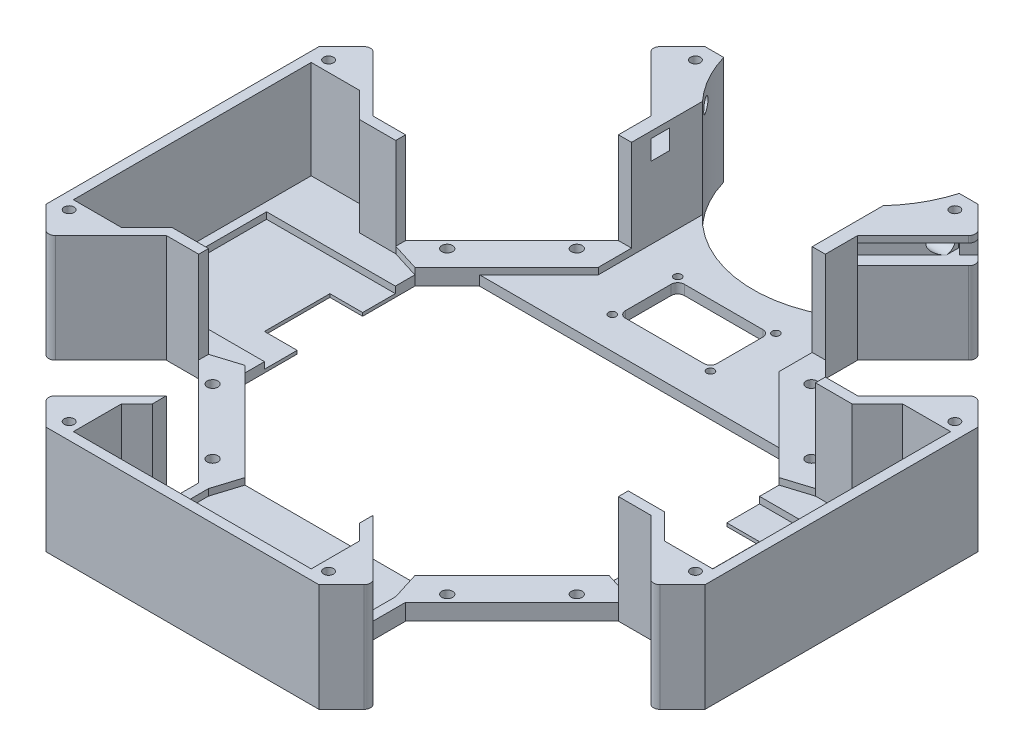
SolidWorks part; units mm, degrees
ref_plane "Front Plane" through (0, 0, 0) normal (0, 0, 1) x (1, 0, 0)
ref_plane "Top Plane" through (0, 0, 0) normal (0, 1, 0) x (1, 0, 0)
ref_plane "Right Plane" through (0, 0, 0) normal (1, 0, 0) x (0, 0, -1)
sketch "Sketch1" plane through (0, 0, 0) normal (0, 1, 0) x (1, 0, 0)
  line L1 (-41.7125, 100.7029) -> (-100.7029, 41.7125)
  line L2 (-100.7029, 41.7125) -> (-100.7029, -41.7125)
  line L3 (-100.7029, -41.7125) -> (-41.7125, -100.7029)
  line L4 (-41.7125, -100.7029) -> (41.7125, -100.7029)
  line L5 (41.7125, -100.7029) -> (100.7029, -41.7125)
  line L6 (100.7029, -41.7125) -> (100.7029, 41.7125)
  line L7 (100.7029, 41.7125) -> (41.7125, 100.7029)
  line L8 (41.7125, 100.7029) -> (-41.7125, 100.7029)
  circle A0 centre (0, 0) radius 100.7029 construction
  circle A1 centre (0, 0) radius 109 construction
  dimension "D1" = 218
extrude "Boss-Extrude1" add sketch "Sketch1" along normal blind 3
sketch "Sketch2" plane through (0, 3, 0) normal (0, 1, 0) x (1, 0, 0)
  line L5 (-92.4209, 49.9945) -> (-49.9945, 92.4209)
  line L6 (-92.4209, 49.9945) -> (-69.0864, 26.66)
  line L7 (-49.9945, 92.4209) -> (-26.66, 69.0864)
  line L8 (-69.0864, 26.66) -> (-26.66, 69.0864)
  line L9 (-41.7125, 100.7029) -> (-100.7029, 41.7125) construction
  line L10 (0, 0) -> (-71.2077, 71.2077) construction
  line L11 (100.7029, 41.7125) -> (41.7125, 100.7029) construction
  line L12 (49.9945, 92.4209) -> (92.4209, 49.9945)
  line L13 (49.9945, 92.4209) -> (26.66, 69.0864)
  line L14 (26.66, 69.0864) -> (69.0864, 26.66)
  line L15 (92.4209, 49.9945) -> (69.0864, 26.66)
  line L16 (92.4209, -49.9945) -> (49.9945, -92.4209)
  line L17 (92.4209, -49.9945) -> (69.0864, -26.66)
  line L18 (69.0864, -26.66) -> (26.66, -69.0864)
  line L19 (49.9945, -92.4209) -> (26.66, -69.0864)
  line L20 (-49.9945, -92.4209) -> (-92.4209, -49.9945)
  line L21 (-49.9945, -92.4209) -> (-26.66, -69.0864)
  line L22 (-26.66, -69.0864) -> (-69.0864, -26.66)
  line L23 (-92.4209, -49.9945) -> (-69.0864, -26.66)
  circle A0 centre (-55.6513, 35.8523) radius 1.65
  circle A1 centre (-35.8523, 55.6513) radius 1.65
  circle A2 centre (55.6513, 35.8523) radius 1.65
  circle A3 centre (35.8523, 55.6513) radius 1.65
  circle A4 centre (35.8523, -55.6513) radius 1.65
  circle A5 centre (55.6513, -35.8523) radius 1.65
  circle A6 centre (-55.6513, -35.8523) radius 1.65
  circle A7 centre (-35.8523, -55.6513) radius 1.65
  point P42 (0, 0)
  dimension "D7" = 3.3
  dimension "D8" = 3.3
  dimension "D1" = 60
  dimension "D2" = 33
  dimension "D3" = 3
  dimension "D4" = 3
  dimension "D5" = 28
  dimension "D6" = 14
  dimension "D10" = 71.7047
  dimension "D11" = 67.7029
  dimension "D9" = 4
extrude "Cut-Extrude1" cut sketch "Sketch2" against normal up to next
sketch "Sketch3" plane through (0, 3, 0) normal (0, 1, 0) x (1, 0, 0)
  line L0 (0, 0) -> (0, 50000) construction
  line L1 (-1015.9137, 73.7029) -> (48984.0863, 73.7029) construction
  line L2 (41.7125, 100.7029) -> (-41.7125, 100.7029) construction
  circle A0 centre (0, 111.2029) radius 37.5
  dimension "D1" = 75
  dimension "D2" = 27
extrude "Cut-Extrude2" cut sketch "Sketch3" against normal up to next
chamfer "Chamfer1" distance 8 angle 45 8 edges at (92.4209, 1.5, 49.9945) (49.9945, 1.5, 92.4209) (-49.9945, 1.5, 92.4209) (-92.4209, 1.5, 49.9945) (-92.4209, 1.5, -49.9945) (92.4209, 1.5, -49.9945) (-49.9945, 1.5, -92.4209) (49.9945, 1.5, -92.4209)
chamfer "Chamfer2" distance 7 angle 45 8 edges at (-69.0864, 1.5, 26.66) (-26.66, 1.5, 69.0864) (26.66, 1.5, 69.0864) (69.0864, 1.5, 26.66) (69.0864, 1.5, -26.66) (26.66, 1.5, -69.0864) (-69.0864, 1.5, -26.66) (-26.66, 1.5, -69.0864)
sketch "Sketch4" plane through (0, 3, 0) normal (0, 1, 0) x (1, 0, 0)
  line L0 (-36, 100.7029) -> (-41.7125, 100.7029) construction
  line L1 (-41.7125, 100.7029) -> (-44.3376, 98.0777) construction
  line L2 (41.7125, 100.7029) -> (36, 100.7029) construction
  line L3 (44.3376, 98.0777) -> (41.7125, 100.7029) construction
  circle A0 centre (-39.6414, 95.7029) radius 1.5
  circle A1 centre (39.6414, 95.7029) radius 1.5
  circle A2 centre (95.7029, 39.6414) radius 1.5
  circle A3 centre (95.7029, -39.6414) radius 1.5
  circle A4 centre (39.6414, -95.7029) radius 1.5
  circle A5 centre (-39.6414, -95.7029) radius 1.5
  circle A6 centre (-95.7029, -39.6414) radius 1.5
  circle A7 centre (-95.7029, 39.6414) radius 1.5
  point P22 (0, 0)
  dimension "D3" = 3
  dimension "D1" = 5
  dimension "D2" = 5
  dimension "D5" = 5
  dimension "D6" = 5
  dimension "D4" = 8
extrude "Cut-Extrude3" cut sketch "Sketch4" against normal up to next
sketch "Sketch5" plane through (0, 3, 0) normal (0, 1, 0) x (1, 0, 0)
  line L0 (-45.7518, 35.8523) -> (-55.6513, 25.9528)
  line L1 (-55.6513, 25.9528) -> (-55.6513, -25.9528)
  line L2 (-55.6513, -25.9528) -> (-25.9528, -55.6513)
  line L3 (-25.9528, -55.6513) -> (25.9528, -55.6513)
  line L4 (25.9528, -55.6513) -> (55.6513, -25.9528)
  line L5 (55.6513, -25.9528) -> (55.6513, 25.9528)
  line L6 (55.6513, 25.9528) -> (45.7518, 35.8523)
  line L7 (45.7518, 35.8523) -> (-45.7518, 35.8523)
  line L8 (-55.6513, 35.8523) -> (55.6513, 35.8523) construction
  line L9 (55.6513, 35.8523) -> (55.6513, -35.8523) construction
  line L10 (55.6513, -35.8523) -> (35.8523, -55.6513) construction
  line L11 (35.8523, -55.6513) -> (-35.8523, -55.6513) construction
  line L12 (-35.8523, -55.6513) -> (-55.6513, -35.8523) construction
  line L13 (-55.6513, -35.8523) -> (-55.6513, 35.8523) construction
  line L14 (-64.1366, 31.6097) -> (-31.6097, 64.1366) construction
  line L15 (31.6097, 64.1366) -> (64.1366, 31.6097) construction
  line L16 (-31.6097, -64.1366) -> (-64.1366, -31.6097) construction
  line L17 (64.1366, -31.6097) -> (31.6097, -64.1366) construction
  dimension "D1" = 10
  dimension "D2" = 10
  dimension "D3" = 10
  dimension "D4" = 10
extrude "Cut-Extrude4" cut sketch "Sketch5" against normal up to next
sketch "Sketch7" plane through (0, 3, 0) normal (0, 1, 0) x (1, 0, 0)
  line L0 (-64.1366, 31.6097) -> (-74.0361, 31.6097)
  line L1 (-74.0361, 31.6097) -> (-86.764, 44.3376)
  line L2 (-86.764, 44.3376) -> (-98.0777, 44.3376)
  line L3 (-98.0777, 44.3376) -> (-100.7029, 41.7125)
  line L4 (-100.7029, 41.7125) -> (-100.7029, -41.7125)
  line L5 (-100.7029, -41.7125) -> (-98.0777, -44.3376)
  line L6 (-98.0777, -44.3376) -> (-86.764, -44.3376)
  line L7 (-86.764, -44.3376) -> (-74.0361, -31.6097)
  line L8 (-74.0361, -31.6097) -> (-64.1366, -31.6097)
  line L9 (-64.1366, -31.6097) -> (-64.1366, -28.6097)
  line L10 (-64.1366, -28.6097) -> (-75.2787, -28.6097)
  line L11 (-75.2787, -28.6097) -> (-83.0067, -36.3376)
  line L12 (-83.0067, -36.3376) -> (-97.7029, -36.3376)
  line L13 (-97.7029, -36.3376) -> (-97.7029, 36.3376)
  line L14 (-97.7029, 36.3376) -> (-83.0067, 36.3376)
  line L15 (-83.0067, 36.3376) -> (-75.2787, 28.6097)
  line L16 (-75.2787, 28.6097) -> (-64.1366, 28.6097)
  line L17 (-64.1366, 28.6097) -> (-64.1366, 31.6097)
  line L18 (-31.6097, -64.1366) -> (-31.6097, -74.0361)
  line L19 (-31.6097, -74.0361) -> (-44.3376, -86.764)
  line L20 (-44.3376, -86.764) -> (-44.3376, -98.0777)
  line L21 (-44.3376, -98.0777) -> (-41.7125, -100.7029)
  line L22 (-41.7125, -100.7029) -> (41.7125, -100.7029)
  line L23 (41.7125, -100.7029) -> (44.3376, -98.0777)
  line L24 (44.3376, -98.0777) -> (44.3376, -86.764)
  line L25 (44.3376, -86.764) -> (31.6097, -74.0361)
  line L26 (31.6097, -74.0361) -> (31.6097, -64.1366)
  line L27 (31.6097, -64.1366) -> (28.6097, -64.1366)
  line L28 (28.6097, -64.1366) -> (28.6097, -75.2787)
  line L29 (28.6097, -75.2787) -> (36.3376, -83.0067)
  line L30 (36.3376, -83.0067) -> (36.3376, -97.7029)
  line L31 (36.3376, -97.7029) -> (-36.3376, -97.7029)
  line L32 (-36.3376, -97.7029) -> (-36.3376, -83.0067)
  line L33 (-36.3376, -83.0067) -> (-28.6097, -75.2787)
  line L34 (-28.6097, -75.2787) -> (-28.6097, -64.1366)
  line L35 (-28.6097, -64.1366) -> (-31.6097, -64.1366)
  line L36 (64.1366, -31.6097) -> (74.0361, -31.6097)
  line L37 (74.0361, -31.6097) -> (86.764, -44.3376)
  line L38 (86.764, -44.3376) -> (98.0777, -44.3376)
  line L39 (98.0777, -44.3376) -> (100.7029, -41.7125)
  line L40 (100.7029, -41.7125) -> (100.7029, 41.7125)
  line L41 (100.7029, 41.7125) -> (98.0777, 44.3376)
  line L42 (98.0777, 44.3376) -> (86.764, 44.3376)
  line L43 (86.764, 44.3376) -> (74.0361, 31.6097)
  line L44 (74.0361, 31.6097) -> (64.1366, 31.6097)
  line L45 (64.1366, 31.6097) -> (64.1366, 28.6097)
  line L46 (64.1366, 28.6097) -> (75.2787, 28.6097)
  line L47 (75.2787, 28.6097) -> (83.0067, 36.3376)
  line L48 (83.0067, 36.3376) -> (97.7029, 36.3376)
  line L49 (97.7029, 36.3376) -> (97.7029, -36.3376)
  line L50 (97.7029, -36.3376) -> (83.0067, -36.3376)
  line L51 (83.0067, -36.3376) -> (75.2787, -28.6097)
  line L52 (75.2787, -28.6097) -> (64.1366, -28.6097)
  line L53 (64.1366, -28.6097) -> (64.1366, -31.6097)
  line L54 (0, 0) -> (-64.1366, 28.6097) construction
  line L55 (0, 0) -> (-28.6097, -64.1366) construction
  line L57 (-36, 100.7029) -> (-41.7125, 100.7029)
  line L58 (-41.7125, 100.7029) -> (-44.3376, 98.0777)
  line L59 (-44.3376, 98.0777) -> (-44.3376, 86.764)
  line L60 (-44.3376, 86.764) -> (-31.6097, 74.0361)
  line L61 (-31.6097, 74.0361) -> (-31.6097, 64.1366)
  line L62 (-31.6097, 64.1366) -> (-27.6097, 64.1366)
  line L63 (-27.6097, 64.1366) -> (-27.6097, 85.8266)
  line L64 (0, -888.7971) -> (0, 49111.2029) construction
  line L65 (27.6097, 64.1366) -> (27.6097, 85.8266)
  line L66 (31.6097, 64.1366) -> (27.6097, 64.1366)
  line L67 (31.6097, 74.0361) -> (31.6097, 64.1366)
  line L68 (44.3376, 86.764) -> (31.6097, 74.0361)
  line L69 (44.3376, 98.0777) -> (44.3376, 86.764)
  line L70 (41.7125, 100.7029) -> (44.3376, 98.0777)
  line L71 (36, 100.7029) -> (41.7125, 100.7029)
  arc A0 (-36, 100.7029) -> (-27.6097, 85.8266) centre (0, 111.2029) ccw
  arc A1 (36, 100.7029) -> (27.6097, 85.8266) centre (0, 111.2029) cw
  circle A10 centre (-39.6414, 95.7029) radius 1.5
  circle A11 centre (39.6414, 95.7029) radius 1.5
  circle A12 centre (95.7029, 39.6414) radius 1.5
  circle A13 centre (95.7029, -39.6414) radius 1.5
  circle A14 centre (39.6414, -95.7029) radius 1.5
  circle A15 centre (-39.6414, -95.7029) radius 1.5
  circle A16 centre (-95.7029, -39.6414) radius 1.5
  circle A17 centre (-95.7029, 39.6414) radius 1.5
  point P4 (-92.4209, 44.3376)
  point P29 (-92.4209, -44.3376)
  dimension "D14" = 3
  dimension "D15" = 3
  dimension "D16" = 3
  dimension "D17" = 3
  dimension "D18" = 3
  dimension "D19" = 3
  dimension "D20" = 3
  dimension "D21" = 3
  dimension "D1" = 3
  dimension "D2" = 8
  dimension "D3" = 8
  dimension "D4" = 3
  dimension "D5" = 3
  dimension "D6" = 3
  dimension "D7" = 3
  dimension "D9" = 90
  dimension "D10" = 90
  dimension "D11" = 28.6097
  dimension "D12" = 64.1366
  dimension "D13" = 4
  dimension "D8" = 3
extrude "Boss-Extrude2" add sketch "Sketch7" along normal blind 30
sketch "Sketch8" plane through (0, 0, 0) normal (0, -1, 0) x (1, 0, 0)
  line L0 (-41.7125, 100.7029) -> (41.7125, 100.7029) construction
  line L1 (-22, 83.7029) -> (-2, 83.7029)
  line L2 (-22, 83.7029) -> (-22, 95.7029)
  line L3 (-22, 95.7029) -> (-2, 95.7029)
  line L4 (-2, 83.7029) -> (-2, 95.7029)
  line L5 (-22, 83.7029) -> (-2, 95.7029) construction
  line L6 (-22, 95.7029) -> (-2, 83.7029) construction
  line L7 (0, -1000) -> (0, 49000) construction
  line L8 (22, 95.7029) -> (2, 83.7029) construction
  line L9 (22, 83.7029) -> (2, 95.7029) construction
  line L10 (2, 83.7029) -> (2, 95.7029)
  line L11 (22, 95.7029) -> (2, 95.7029)
  line L12 (22, 83.7029) -> (22, 95.7029)
  line L13 (22, 83.7029) -> (2, 83.7029)
  point P0 (-12, 89.7029)
  point P15 (12, 89.7029)
  dimension "D1" = 20
  dimension "D2" = 12
  dimension "D3" = 5
  dimension "D4" = 2
extrude "Cut-Extrude5" cut sketch "Sketch8" against normal up to next
sketch "Sketch10" plane through (0, 3, 0) normal (0, 1, 0) x (1, 0, 0)
  line L1 (-95, -20) -> (95, -20)
  line L2 (-95, -20) -> (-95, 20)
  line L3 (-95, 20) -> (95, 20)
  line L4 (95, -20) -> (95, 20)
  line L5 (-95, -20) -> (95, 20) construction
  line L6 (-95, 20) -> (95, -20) construction
  point P0 (0, 0)
  dimension "D1" = 190
  dimension "D2" = 40
extrude "Cut-Extrude6" cut sketch "Sketch10" against normal blind 2
sketch "Sketch11" plane through (0, 3, 0) normal (0, 1, 0) x (1, 0, 0)
  line L0 (-31.6097, 64.1366) -> (-64.1366, 31.6097)
  line L1 (-64.1366, 31.6097) -> (-64.1366, 28.6097)
  line L2 (-64.1366, 28.6097) -> (-55.6513, 25.9528)
  line L3 (-55.6513, 25.9528) -> (-27.6097, 53.9945)
  line L4 (-27.6097, 53.9945) -> (-27.6097, 64.1366)
  line L5 (-27.6097, 64.1366) -> (-31.6097, 64.1366)
  line L6 (-28.6097, -64.1366) -> (-25.9528, -55.6513)
  line L7 (-25.9528, -55.6513) -> (-55.6513, -25.9528)
  line L8 (-55.6513, -25.9528) -> (-64.1366, -28.6097)
  line L9 (-64.1366, -28.6097) -> (-64.1366, -31.6097)
  line L10 (-64.1366, -31.6097) -> (-31.6097, -64.1366)
  line L11 (-31.6097, -64.1366) -> (-28.6097, -64.1366)
  line L12 (0, -1000) -> (0, 49000) construction
  line L13 (31.6097, -64.1366) -> (28.6097, -64.1366)
  line L14 (64.1366, -31.6097) -> (31.6097, -64.1366)
  line L15 (64.1366, -28.6097) -> (64.1366, -31.6097)
  line L16 (55.6513, -25.9528) -> (64.1366, -28.6097)
  line L17 (25.9528, -55.6513) -> (55.6513, -25.9528)
  line L18 (28.6097, -64.1366) -> (25.9528, -55.6513)
  line L19 (27.6097, 64.1366) -> (31.6097, 64.1366)
  line L20 (27.6097, 53.9945) -> (27.6097, 64.1366)
  line L21 (55.6513, 25.9528) -> (27.6097, 53.9945)
  line L22 (64.1366, 28.6097) -> (55.6513, 25.9528)
  line L23 (64.1366, 31.6097) -> (64.1366, 28.6097)
  line L24 (31.6097, 64.1366) -> (64.1366, 31.6097)
  circle A0 centre (-35.8523, 55.6513) radius 1.65
  circle A1 centre (-55.6513, 35.8523) radius 1.65
  circle A2 centre (-55.6513, -35.8523) radius 1.65
  circle A3 centre (-35.8523, -55.6513) radius 1.65
  circle A4 centre (35.8523, -55.6513) radius 1.65
  circle A5 centre (55.6513, -35.8523) radius 1.65
  circle A6 centre (55.6513, 35.8523) radius 1.65
  circle A7 centre (35.8523, 55.6513) radius 1.65
  dimension "D1" = 3.3
  dimension "D2" = 3.3
  dimension "D3" = 3.3
  dimension "D4" = 3.3
  dimension "D5" = 3.3
  dimension "D6" = 3.3
  dimension "D7" = 3.3
  dimension "D8" = 3.3
extrude "Boss-Extrude4" add sketch "Sketch11" along normal blind 2
sketch "Sketch12" plane through (0, 33, 0) normal (0, 1, 0) x (1, 0, 0)
  line L0 (-36.3376, -83.0067) -> (-28.6097, -75.2787) construction
  line L1 (-28.6097, -64.1366) -> (-31.6097, -64.1366)
  line L2 (-28.6097, -64.1366) -> (-28.6097, -78.2787)
  line L3 (-28.6097, -78.2787) -> (-31.6097, -78.2787)
  line L4 (-31.6097, -64.1366) -> (-31.6097, -78.2787)
  line L5 (-31.6097, -64.1366) -> (-31.6097, -74.0361) construction
  line L6 (28.6097, -75.2787) -> (36.3376, -83.0067) construction
  line L7 (28.6097, -64.1366) -> (31.6097, -64.1366)
  line L8 (28.6097, -64.1366) -> (28.6097, -78.2787)
  line L9 (28.6097, -78.2787) -> (31.6097, -78.2787)
  line L10 (31.6097, -64.1366) -> (31.6097, -78.2787)
  line L11 (31.6097, -74.0361) -> (31.6097, -64.1366) construction
extrude "Cut-Extrude7" cut sketch "Sketch12" against normal up to surface (28 mm away) up to face at (-45.0161, 5, 45.0161)
sketch "Sketch13" plane through (0, 0, 0) normal (0, -1, 0) x (-1, 0, 0)
  line L0 (35.8523, 55.6513) -> (-35.8523, 55.6513) construction
  line L1 (15, 65.6513) -> (-15, 65.6513) construction
  line L2 (15, 65.6513) -> (15, 45.6513) construction
  line L3 (15, 45.6513) -> (-15, 45.6513) construction
  line L4 (-15, 65.6513) -> (-15, 45.6513) construction
  line L5 (15, 65.6513) -> (-15, 45.6513) construction
  line L6 (15, 45.6513) -> (-15, 65.6513) construction
  line L9 (12, 64.6513) -> (-12, 64.6513)
  line L10 (14, 62.6513) -> (14, 48.6513)
  line L11 (12, 46.6513) -> (-12, 46.6513)
  line L12 (-14, 62.6513) -> (-14, 48.6513)
  line L13 (14, 64.6513) -> (-14, 46.6513) construction
  line L14 (14, 46.6513) -> (-14, 64.6513) construction
  circle A1 centre (15, 45.6513) radius 1.15
  circle A2 centre (-15, 45.6513) radius 1.15
  circle A3 centre (15, 65.6513) radius 1.15
  circle A4 centre (-15, 65.6513) radius 1.15
  arc A5 (12, 64.6513) -> (14, 62.6513) centre (12, 62.6513) cw
  arc A6 (-12, 64.6513) -> (-14, 62.6513) centre (-12, 62.6513) ccw
  arc A7 (-12, 46.6513) -> (-14, 48.6513) centre (-12, 48.6513) cw
  arc A8 (14, 48.6513) -> (12, 46.6513) centre (12, 48.6513) cw
  point P0 (0, 55.6513)
  point P14 (0, 55.6513)
  dimension "D3" = 2.3
  dimension "D4" = 2.3
  dimension "D5" = 2.3
  dimension "D6" = 2.3
  dimension "D9" = 2
  dimension "D1" = 20
  dimension "D2" = 30
  dimension "D7" = 2
  dimension "D8" = 2
extrude "Cut-Extrude8" cut sketch "Sketch13" against normal up to next
sketch "Sketch14" plane through (-44.3376, 0, 0) normal (-1, 0, 0) x (0, 0, 1)
  line L1 (-86.764, 33) -> (-86.764, 0) construction
  line L2 (-98.0777, 33) -> (-86.764, 33) construction
  circle A0 centre (-90.264, 28) radius 2
  dimension "D3" = 4
  dimension "D1" = 5
  dimension "D2" = 3.5
extrude "Cut-Extrude9" cut sketch "Sketch14" against normal through all both and the other way through all
sketch "Sketch15" plane through (-44.3376, 0, 0) normal (-1, 0, 0) x (0, 0, 1)
  circle A0 centre (-90.264, 28) radius 3
  dimension "D1" = 6
extrude "Cut-Extrude10" cut sketch "Sketch15" against normal blind 10
sketch "Sketch16" plane through (0, 0, -64.1366) normal (0, 0, 1) x (1, 0, 0)
  line L0 (-44.3376, 33) -> (-44.3376, 0) construction
  line L1 (-44.3376, 31) -> (-42.3376, 31)
  line L2 (-44.3376, 31) -> (-44.3376, 25)
  line L3 (-44.3376, 25) -> (-42.3376, 25)
  line L4 (-42.3376, 31) -> (-42.3376, 25)
  line L5 (-44.3376, 33) -> (-31.6097, 33) construction
  dimension "D1" = 2
  dimension "D2" = 6
  dimension "D3" = 2
extrude "Cut-Extrude11" cut sketch "Sketch16" against normal blind 30
sketch "Sketch17" plane through (44.3376, 0, 0) normal (1, 0, 0) x (0, 0, -1)
  circle A0 centre (90.264, 28) radius 3
  dimension "D1" = 6
extrude "Cut-Extrude12" cut sketch "Sketch17" against normal blind 10
sketch "Sketch18" plane through (0, 0, -64.1366) normal (0, 0, 1) x (1, 0, 0)
  line L0 (44.3376, 0) -> (44.3376, 33) construction
  line L1 (44.3376, 31) -> (42.3376, 31)
  line L2 (44.3376, 31) -> (44.3376, 25)
  line L3 (44.3376, 25) -> (42.3376, 25)
  line L4 (42.3376, 31) -> (42.3376, 25)
  dimension "D1" = 2
  dimension "D2" = 6
  dimension "D3" = 2
extrude "Cut-Extrude13" cut sketch "Sketch18" against normal blind 30 contours L2 L3 L4 L1
sketch "Sketch21" plane through (0, 0, 0) normal (0, 1, 0) x (1, 0, 0)
  line L0 (-98.0777, 44.3376) -> (-93.8351, 48.5803)
  line L1 (-91.0067, 48.5803) -> (-86.764, 44.3376)
  line L2 (-86.764, 44.3376) -> (-98.0777, 44.3376)
  line L3 (-44.3376, 86.764) -> (-48.5803, 91.0067)
  line L4 (-48.5803, 93.8351) -> (-44.3376, 98.0777)
  line L5 (-44.3376, 98.0777) -> (-44.3376, 86.764)
  line L6 (44.3376, 86.764) -> (48.5803, 91.0067)
  line L7 (48.5803, 93.8351) -> (44.3376, 98.0777)
  line L8 (44.3376, 98.0777) -> (44.3376, 86.764)
  line L9 (86.764, 44.3376) -> (91.0067, 48.5803)
  line L10 (93.8351, 48.5803) -> (98.0777, 44.3376)
  line L11 (98.0777, 44.3376) -> (86.764, 44.3376)
  line L12 (86.764, -44.3376) -> (91.0067, -48.5803)
  line L13 (93.8351, -48.5803) -> (98.0777, -44.3376)
  line L14 (98.0777, -44.3376) -> (86.764, -44.3376)
  line L15 (44.3376, -86.764) -> (48.5803, -91.0067)
  line L16 (48.5803, -93.8351) -> (44.3376, -98.0777)
  line L17 (44.3376, -98.0777) -> (44.3376, -86.764)
  line L18 (44.3376, -86.764) -> (31.6097, -74.0361) construction
  line L19 (100.7029, 41.7125) -> (98.0777, 44.3376) construction
  line L20 (-74.0361, 31.6097) -> (-86.764, 44.3376) construction
  line L21 (-44.3376, -98.0777) -> (-48.5803, -93.8351)
  line L22 (-48.5803, -91.0067) -> (-44.3376, -86.764)
  line L23 (-44.3376, -86.764) -> (-44.3376, -98.0777)
  line L24 (-44.3376, -98.0777) -> (-41.7125, -100.7029) construction
  line L25 (-98.0777, -44.3376) -> (-93.8351, -48.5803)
  line L26 (-91.0067, -48.5803) -> (-86.764, -44.3376)
  line L27 (-86.764, -44.3376) -> (-98.0777, -44.3376)
  line L28 (-86.764, -44.3376) -> (-74.0361, -31.6097) construction
  line L29 (-100.7029, -41.7125) -> (-98.0777, -44.3376) construction
  arc A0 (-93.8351, -48.5803) -> (-91.0067, -48.5803) centre (-92.4209, -47.1661) ccw
  arc A1 (-48.5803, -93.8351) -> (-48.5803, -91.0067) centre (-47.1661, -92.4209) cw
  arc A2 (48.5803, -91.0067) -> (48.5803, -93.8351) centre (47.1661, -92.4209) cw
  arc A3 (91.0067, -48.5803) -> (93.8351, -48.5803) centre (92.4209, -47.1661) ccw
  arc A4 (91.0067, 48.5803) -> (93.8351, 48.5803) centre (92.4209, 47.1661) cw
  arc A5 (48.5803, 91.0067) -> (48.5803, 93.8351) centre (47.1661, 92.4209) ccw
  arc A6 (-93.8351, 48.5803) -> (-91.0067, 48.5803) centre (-92.4209, 47.1661) cw
  arc A7 (-48.5803, 91.0067) -> (-48.5803, 93.8351) centre (-47.1661, 92.4209) cw
  dimension "D1" = 2
extrude "Boss-Extrude5" add sketch "Sketch21" along normal up to surface (33 mm away) up to face at (-95.7029, 33, 41.1414)
sketch "Sketch22" plane through (71.2077, 0, -71.2077) normal (0.7071, 0, -0.7071) x (-0.7071, 0, -0.7071)
  line L0 (30, 33) -> (30, 0) construction
  line L1 (30, 31) -> (34, 31)
  line L2 (30, 31) -> (30, 25)
  line L3 (30, 25) -> (34, 25)
  line L4 (34, 31) -> (34, 25)
  line L5 (32, 33) -> (32, 0) construction
  point P8 (0, 0)
  point P15 (0, 0)
  dimension "D1" = 2
extrude "Cut-Extrude15" cut sketch "Sketch22" against normal up to surface (27.6569 mm away)
sketch "Sketch23" plane through (0, 0, -100.7029) normal (0, 0, -1) x (-1, 0, 0)
  line L0 (-41.7125, 33) -> (-41.7125, 0) construction
  line L1 (-41.7125, 31) -> (-49.1661, 31)
  line L2 (-41.7125, 31) -> (-41.7125, 25)
  line L3 (-41.7125, 25) -> (-49.1661, 25)
  line L4 (-49.1661, 31) -> (-49.1661, 25)
  line L5 (-47.1661, 31) -> (-48.5803, 31) construction
sketch "Sketch24" plane through (-71.2077, 0, -71.2077) normal (-0.7071, 0, -0.7071) x (-0.7071, 0, 0.7071)
  line L0 (-30, 0) -> (-30, 33) construction
  line L1 (-30, 31) -> (-34, 31)
  line L2 (-30, 31) -> (-30, 25)
  line L3 (-30, 25) -> (-34, 25)
  line L4 (-34, 31) -> (-34, 25)
  line L5 (-32, 33) -> (-32, 0) construction
  dimension "D1" = 2
extrude "Cut-Extrude17" cut sketch "Sketch24" against normal up to surface (31.6569 mm away)
sketch "Sketch25" plane through (0, 1, 0) normal (0, 1, 0) x (1, 0, 0)
  line L0 (-55.6513, 20) -> (-55.6513, -20) construction
  line L1 (-65.6513, -10) -> (65.6513, -10)
  line L2 (-65.6513, -10) -> (-65.6513, 10)
  line L3 (-65.6513, 10) -> (65.6513, 10)
  line L4 (65.6513, -10) -> (65.6513, 10)
  line L5 (-65.6513, -10) -> (65.6513, 10) construction
  line L6 (-65.6513, 10) -> (65.6513, -10) construction
  point P0 (0, 0)
  dimension "D1" = 20
  dimension "D2" = 10
extrude "Cut-Extrude18" cut sketch "Sketch25" against normal blind 20
